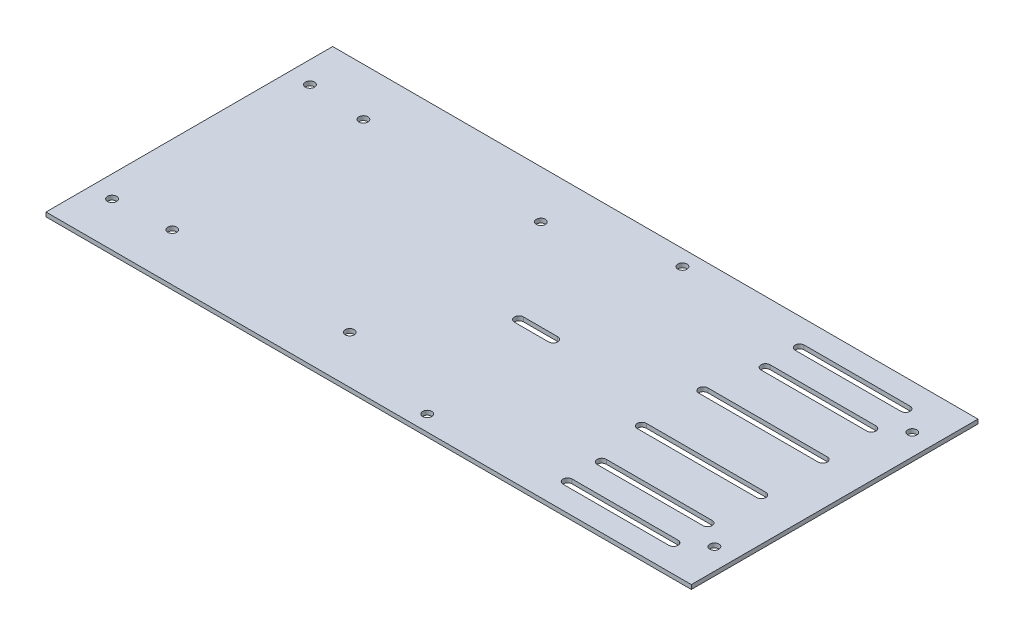
SolidWorks part; units mm, degrees
material "Thornel Mat VMA"
ref_plane "Front Plane" through (0, 0, 0) normal (0, 0, 1) x (1, 0, 0)
ref_plane "Top Plane" through (0, 0, 0) normal (0, 1, 0) x (1, 0, 0)
ref_plane "Right Plane" through (0, 0, 0) normal (1, 0, 0) x (0, 0, -1)
sketch "Sketch1" plane through (0, 0, 0) normal (0, 1, 0) x (1, 0, 0)
  line L0 (-129.54, 0) -> (152.4, 0) construction
  line L1 (-240.157, 106.68) -> (240.157, 106.68)
  line L2 (-240.157, 106.68) -> (-240.157, -106.68)
  line L3 (-240.157, -106.68) -> (240.157, -106.68)
  line L4 (240.157, 106.68) -> (240.157, -73.66)
  line L5 (-240.157, 106.68) -> (240.157, -106.68) construction
  line L6 (-240.157, -106.68) -> (240.157, 106.68) construction
  line L7 (119.507, -22.86) -> (208.407, -22.86) construction
  line L8 (119.507, -19.4818) -> (208.407, -19.4818)
  line L9 (119.507, -26.2382) -> (208.407, -26.2382)
  line L10 (119.507, 22.86) -> (208.407, 22.86) construction
  line L11 (119.507, 19.4818) -> (208.407, 19.4818)
  line L12 (119.507, 26.2382) -> (208.407, 26.2382)
  line L13 (127.762, -60.96) -> (206.502, -60.96) construction
  line L14 (127.762, -57.5818) -> (206.502, -57.5818)
  line L15 (127.762, -64.3382) -> (206.502, -64.3382)
  line L16 (240.157, -73.66) -> (240.157, -106.68)
  line L17 (240.157, -73.66) -> (-240.157, -73.66) construction
  line L18 (127.762, -86.36) -> (206.502, -86.36) construction
  line L19 (127.762, -89.7382) -> (206.502, -89.7382)
  line L20 (127.762, -82.9818) -> (206.502, -82.9818)
  line L21 (127.762, 60.96) -> (206.502, 60.96) construction
  line L22 (127.762, 57.5818) -> (206.502, 57.5818)
  line L23 (127.762, 64.3382) -> (206.502, 64.3382)
  line L24 (127.762, 86.36) -> (206.502, 86.36) construction
  line L25 (127.762, 89.7382) -> (206.502, 89.7382)
  line L26 (127.762, 82.9818) -> (206.502, 82.9818)
  line L27 (5.207, 0) -> (30.607, 0) construction
  line L28 (5.207, 3.3782) -> (30.607, 3.3782)
  line L29 (5.207, -3.3782) -> (30.607, -3.3782)
  arc A0 (119.507, -19.4818) -> (119.507, -26.2382) centre (119.507, -22.86) ccw
  arc A1 (208.407, -26.2382) -> (208.407, -19.4818) centre (208.407, -22.86) ccw
  arc A2 (119.507, 19.4818) -> (119.507, 26.2382) centre (119.507, 22.86) cw
  arc A3 (208.407, 26.2382) -> (208.407, 19.4818) centre (208.407, 22.86) cw
  circle A4 centre (224.282, -73.66) radius 3.3782
  arc A5 (127.762, -57.5818) -> (127.762, -64.3382) centre (127.762, -60.96) ccw
  arc A6 (206.502, -64.3382) -> (206.502, -57.5818) centre (206.502, -60.96) ccw
  arc A7 (127.762, -89.7382) -> (127.762, -82.9818) centre (127.762, -86.36) cw
  arc A8 (206.502, -82.9818) -> (206.502, -89.7382) centre (206.502, -86.36) cw
  circle A9 centre (31.877, -94.9833) radius 3.3782
  circle A10 centre (31.877, 94.9833) radius 3.3782
  arc A11 (127.762, 57.5818) -> (127.762, 64.3382) centre (127.762, 60.96) cw
  arc A12 (206.502, 64.3382) -> (206.502, 57.5818) centre (206.502, 60.96) cw
  arc A13 (127.762, 89.7382) -> (127.762, 82.9818) centre (127.762, 86.36) ccw
  arc A14 (206.502, 82.9818) -> (206.502, 89.7382) centre (206.502, 86.36) ccw
  circle A15 centre (224.282, 73.66) radius 3.3782
  arc A16 (5.207, 3.3782) -> (5.207, -3.3782) centre (5.207, 0) ccw
  arc A17 (30.607, -3.3782) -> (30.607, 3.3782) centre (30.607, 0) ccw
  circle A18 centre (-224.028, 73.66) radius 3.3782
  circle A19 centre (-224.028, -73.66) radius 3.3782
  circle A20 centre (-181.737, 71.12) radius 3.3782
  circle A21 centre (-49.657, 71.12) radius 3.3782
  circle A22 centre (-49.657, -71.12) radius 3.3782
  circle A23 centre (-181.737, -71.12) radius 3.3782
  point P0 (0, 0)
  point P10 (163.957, -22.86)
  point P17 (163.957, 22.86)
  point P25 (167.132, -60.96)
  point P35 (167.132, -86.36)
  point P46 (167.132, 60.96)
  point P53 (167.132, 86.36)
  point P62 (17.907, 0)
  point P77 (-181.737, -71.12)
  dimension "D5" = 3.3782
  dimension "D10" = 6.7564
  dimension "D18" = 2
  dimension "D17" = 3.3782
  dimension "D20" = 71.12
  dimension "D22" = 6.7564
  dimension "D23" = 6.7564
  dimension "D2" = 213.36
  dimension "D3" = 22.86
  dimension "D4" = 31.75
  dimension "D6" = 88.9
  dimension "D7" = 33.02
  dimension "D8" = 17.78
  dimension "D9" = 12.7
  dimension "D11" = 15.875
  dimension "D12" = 78.74
  dimension "D13" = 208.28
  dimension "D14" = 94.9833
  dimension "D15" = 25.4
  dimension "D16" = 209.55
  dimension "D19" = 480.314
  dimension "D21" = 58.42
  dimension "D24" = 132.08
  dimension "D25" = 71.12
extrude "Boss-Extrude1" add sketch "Sketch1" along normal blind 3.175
